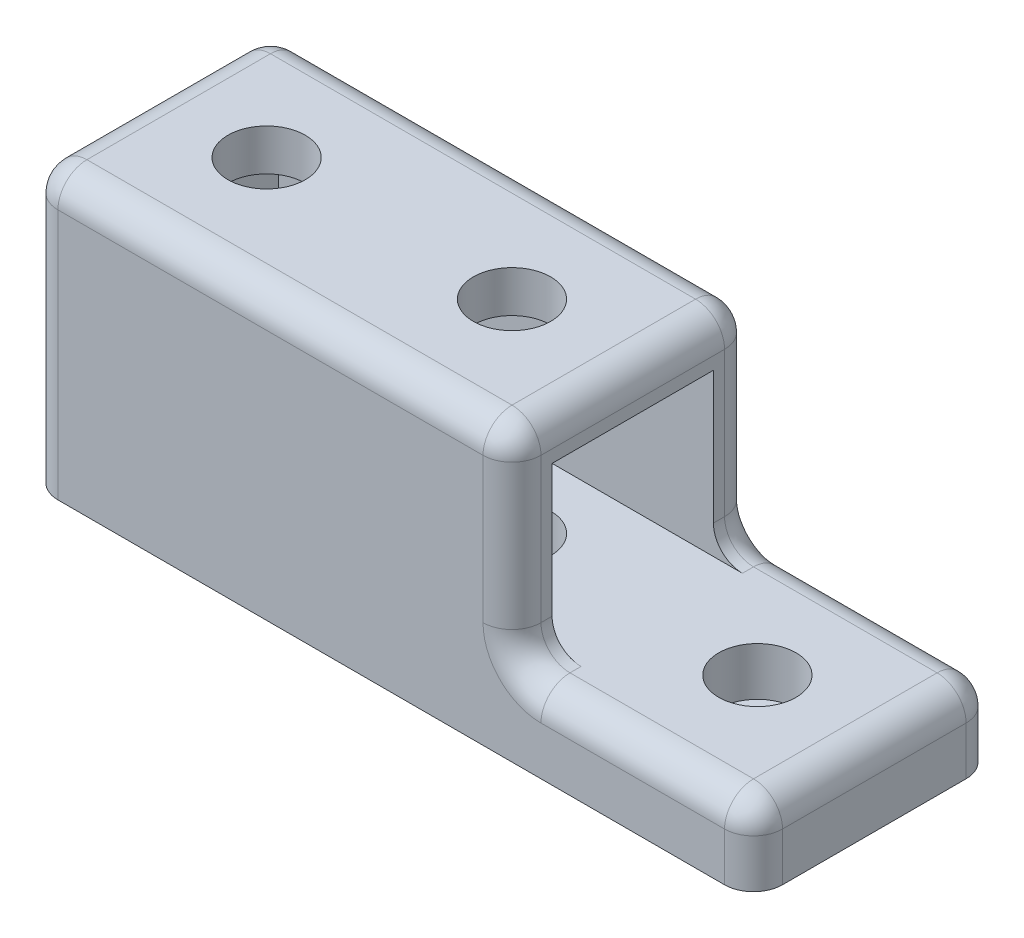
SolidWorks part; units mm, degrees
material "ABS"
ref_plane "Front Plane" through (0, 0, 0) normal (0, 0, 1) x (1, 0, 0)
ref_plane "Top Plane" through (0, 0, 0) normal (0, 1, 0) x (1, 0, 0)
ref_plane "Right Plane" through (0, 0, 0) normal (1, 0, 0) x (0, 0, -1)
sketch "Sketch1" plane through (0, 0, 0) normal (0, 1, 0) x (1, 0, 0)
  line L1 (-37.5, -12.5) -> (37.5, -12.5)
  line L2 (-37.5, -12.5) -> (-37.5, 12.5)
  line L3 (-37.5, 12.5) -> (37.5, 12.5)
  line L4 (37.5, -12.5) -> (37.5, 12.5)
  line L5 (-37.5, -12.5) -> (37.5, 12.5) construction
  line L6 (-37.5, 12.5) -> (37.5, -12.5) construction
  point P0 (0, 0)
  dimension "D1" = 25
  dimension "D2" = 75
extrude "Boss-Extrude1" add sketch "Sketch1" along normal blind 8
sketch "Sketch5" plane through (-37.5, 0, 0) normal (-1, 0, 0) x (0, 0, 1)
  line L1 (-12.5, 8) -> (12.5, 8)
  line L2 (-12.5, 8) -> (-12.5, 29)
  line L3 (-12.5, 29) -> (12.5, 29)
  line L4 (12.5, 8) -> (12.5, 29)
  dimension "D1" = 25
  dimension "D2" = 21
extrude "Boss-Extrude2" add sketch "Sketch5" against normal blind 50
sketch "Sketch7" plane through (12.5, 0, 0) normal (1, 0, 0) x (0, 0, -1)
  line L0 (-8.35, 8) -> (-8.35, 24.7)
  line L5 (-8.35, 24.7) -> (8.35, 24.7)
  line L6 (-8.35, 8) -> (8.35, 8)
  line L7 (8.35, 24.7) -> (8.35, 8)
  line L8 (12.5, 8) -> (-12.5, 8) construction
  point P5 (0, 8)
  dimension "D1" = 16.7
  dimension "D2" = 16.7
extrude "Cut-Extrude3" cut sketch "Sketch7" against normal blind 45
sketch "Sketch4" plane through (0, 0, 0) normal (0, 1, 0) x (1, 0, 0)
  line L0 (-25.4, 0) -> (25.4, 0) construction
  circle A0 centre (0, 0) radius 2.3813
  circle A1 centre (25.4, 0) radius 2.3813
  circle A2 centre (-25.4, 0) radius 2.3813
  point P5 (0, 0)
extrude "Cut-Extrude2" cut sketch "Sketch4" along normal through all
sketch "Sketch3" plane through (0, 8, 0) normal (0, 1, 0) x (1, 0, 0)
  line L0 (-25.4, 0) -> (25.4, 0) construction
  circle A0 centre (0, 0) radius 4
  circle A1 centre (25.4, 0) radius 4
  circle A2 centre (-25.4, 0) radius 4
  point P4 (0, 0)
extrude "Cut-Extrude1" cut sketch "Sketch3" against normal blind 5 and the other way through all
fillet "Fillet1" radius 3 15 edges at (-37.5, 14.5, -12.5) (-37.5, 14.5, 12.5) (-37.5, 29, 0) (12.5, 29, 0) (-12.5, 29, 12.5) (-12.5, 29, -12.5) (25, 8, -12.5) (12.5, 18.5, -12.5) (37.5, 4, -12.5) (37.5, 4, 12.5) (37.5, 8, 0) (25, 8, 12.5) (12.5, 8, 10.425) (12.5, 18.5, 12.5) (12.5, 8, -10.425)
